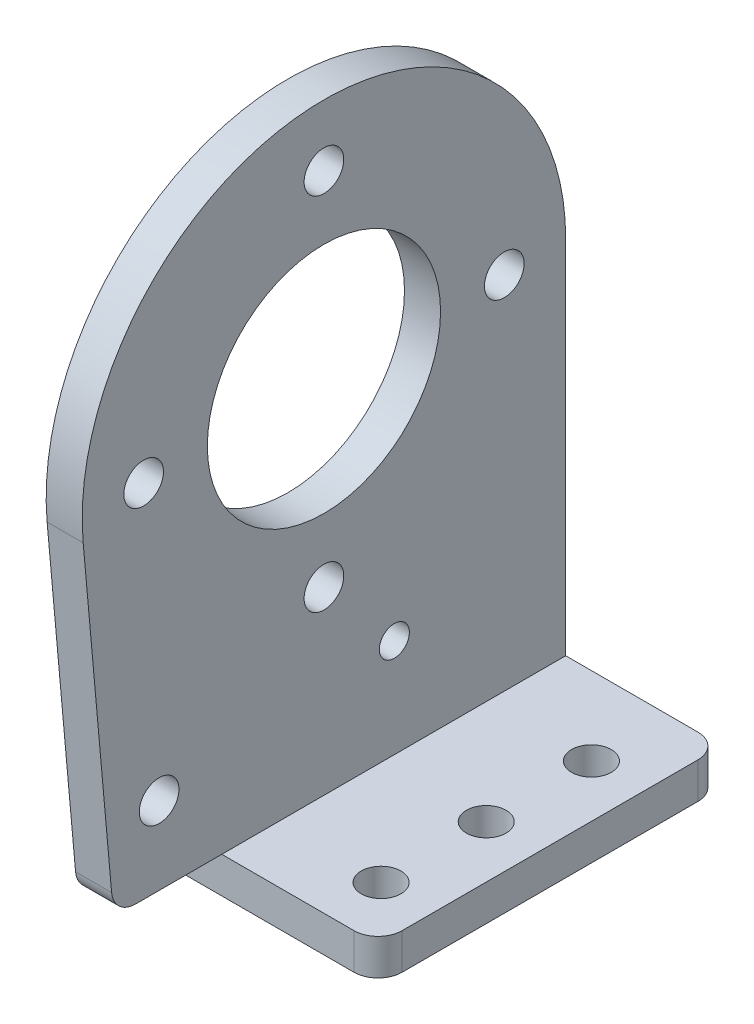
SolidWorks part; units mm, degrees
ref_plane "前视基准面" through (0, 0, 0) normal (0, 0, 1) x (1, 0, 0)
ref_plane "上视基准面" through (0, 0, 0) normal (0, 1, 0) x (1, 0, 0)
ref_plane "右视基准面" through (0, 0, 0) normal (1, 0, 0) x (0, 0, -1)
sketch "草图2" plane through (0, 0, 0) normal (-1, 0, 0) x (0, 0, 1)
  line L0 (-9, 13) -> (-61, 13)
  line L1 (-37.6103, 13) -> (-37.6103, 10)
  line L2 (-61, 10) -> (-9, 10)
  line L5 (-61, 10) -> (-61, 16)
  line L6 (-61, 16) -> (-9, 16)
  line L7 (-9, 10) -> (-9, 16)
extrude "凸台-拉伸5" add sketch "草图2" against normal blind 16 contours L7 L2 L1 L0
sketch "草图3" plane through (0, 13, 0) normal (0, 1, 0) x (1, 0, 0)
  line L0 (11.65, 22.35) -> (11.65, 31.1)
  circle A0 centre (11.65, 31.1) radius 1.65
  circle A4 centre (11.65, 56.35) radius 1.65
  circle A5 centre (11.65, 47.65) radius 1.65
  circle A6 centre (11.65, 22.35) radius 1.65
  circle A7 centre (11.65, 13.6) radius 1.65
extrude "切除-拉伸1" cut sketch "草图3" against normal blind 10
sketch "草图4" plane through (0, 0, 0) normal (1, 0, 0) x (0, 0, -1)
  line L0 (37.6103, 42.9997) -> (37.6103, 13)
  line L3 (0, 0) -> (0, 52.9088)
  line L4 (35.1701, 53.1122) -> (70.1701, 53.1122)
  line L9 (52.6701, 53.1122) -> (16.7421, 64.2983)
  line L10 (0, 13) -> (61, 13)
  line L15 (0, 13) -> (-3.2625, 49.3636)
  line L17 (70, 13) -> (61, 13)
  line L18 (52.6701, 53.1122) -> (61, 13)
  circle A0 centre (17.4998, 57.9997) radius 1.65
  circle A1 centre (32.4998, 42.9997) radius 1.65
  circle A2 centre (17.4998, 27.9997) radius 1.65
  circle A3 centre (2.4998, 42.9997) radius 1.65
  circle A6 centre (17.4998, 42.9997) radius 9.7
  circle A7 centre (17.4998, 42.9997) radius 20.1105
  circle A8 centre (48.125, 48) radius 1.65
  circle A9 centre (23.3549, 21.1974) radius 1.25
  circle A10 centre (53.0261, 18.2423) radius 1.65
  circle A11 centre (3.7886, 19.472) radius 1.65
  circle A12 centre (17.4998, 42.9997) radius 15
  dimension "D1" = 13
  dimension "D2" = 17.4998
  dimension "D3" = 30
  dimension "D4" = 19.4
  dimension "D5" = 40.2211
extrude "凸台-拉伸8" add sketch "草图4" along normal blind 3
fillet "圆角1" radius 2 3 edges at (1.5, 13, 0) (16, 11.5, -37.6103) (16, 11.5, -9)
